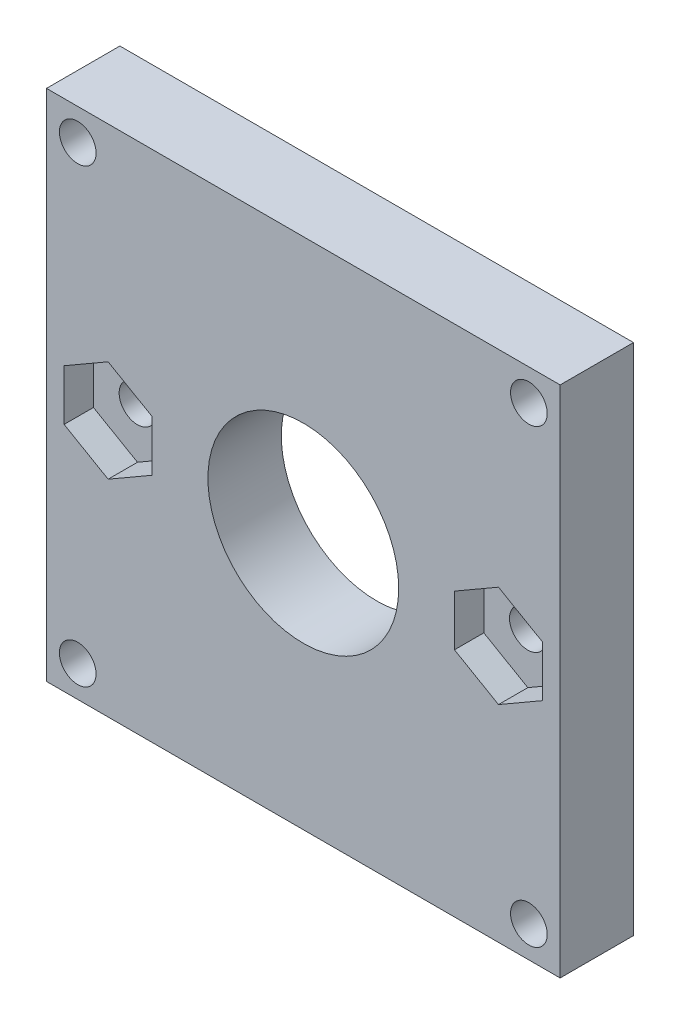
SolidWorks part; units mm, degrees
ref_plane "Alzado" through (0, 0, 0) normal (0, 0, 1) x (1, 0, 0)
ref_plane "Planta" through (0, 0, 0) normal (0, 1, 0) x (1, 0, 0)
ref_plane "Vista lateral" through (0, 0, 0) normal (1, 0, 0) x (0, 0, -1)
sketch "Croquis1" plane through (0, 0, 0) normal (0, 0, 1) x (1, 0, 0)
  line L0 (-17.5, 17.5) -> (-17.5, 13.25) construction
  line L1 (17.5, -17.5) -> (-17.5, -17.5)
  line L2 (17.5, -17.5) -> (17.5, 17.5)
  line L3 (17.5, 17.5) -> (-17.5, 17.5)
  line L4 (-17.5, -17.5) -> (-17.5, 17.5)
  line L5 (17.5, -17.5) -> (-17.5, 17.5) construction
  line L6 (17.5, 17.5) -> (-17.5, -17.5) construction
  line L7 (-17.5, 13.25) -> (-15.37, 13.25) construction
  line L8 (-15.37, 13.25) -> (-15.37, 15.37) construction
  line L9 (17.5, 13.25) -> (15.37, 13.25) construction
  line L10 (15.37, 13.25) -> (15.37, 15.37) construction
  line L11 (15.37, -17.5) -> (15.37, -15.37) construction
  line L12 (-17.5, -15.37) -> (-15.37, -15.37) construction
  line L13 (-13.3, 0) -> (13.3, 0)
  circle A0 centre (-15.37, 15.37) radius 1.25
  circle A1 centre (15.37, 15.37) radius 1.25
  circle A2 centre (15.37, -15.37) radius 1.25
  circle A3 centre (-15.37, -15.37) radius 1.25
  circle A4 centre (0, 0) radius 6.5
  circle A5 centre (13.3, 0) radius 1.25
  circle A6 centre (-13.3, 0) radius 1.25
  point P0 (0, 0)
  point P24 (0, 0)
  dimension "D5" = 2.5
  dimension "D8" = 2.5
  dimension "D10" = 2.5
  dimension "D12" = 2.5
  dimension "D13" = 13
  dimension "D15" = 2.5
  dimension "D16" = 1.25
  dimension "D1" = 35
  dimension "D2" = 4.25
  dimension "D3" = 2.13
  dimension "D4" = 2.12
  dimension "D6" = 2.13
  dimension "D7" = 2.12
  dimension "D9" = 2.13
  dimension "D11" = 2.13
  dimension "D14" = 13.3
extrude "Saliente-Extruir1" add sketch "Croquis1" along normal blind 5
sketch "Croquis2" plane through (0, 0, 5) normal (0, 0, 1) x (1, 0, 0)
  line L1 (-13.3, 3.4641) -> (-16.3, 1.7321)
  line L2 (-16.3, 1.7321) -> (-16.3, -1.7321)
  line L3 (-16.3, -1.7321) -> (-13.3, -3.4641)
  line L4 (-13.3, -3.4641) -> (-10.3, -1.7321)
  line L5 (-10.3, -1.7321) -> (-10.3, 1.7321)
  line L6 (-10.3, 1.7321) -> (-13.3, 3.4641)
  line L7 (13.3, 3.4641) -> (10.3, 1.7321)
  line L8 (10.3, 1.7321) -> (10.3, -1.7321)
  line L9 (10.3, -1.7321) -> (13.3, -3.4641)
  line L10 (13.3, -3.4641) -> (16.3, -1.7321)
  line L11 (16.3, -1.7321) -> (16.3, 1.7321)
  line L12 (16.3, 1.7321) -> (13.3, 3.4641)
  circle A0 centre (-13.3, 0) radius 3 construction
  circle A1 centre (13.3, 0) radius 3 construction
extrude "Cortar-Extruir1" cut sketch "Croquis2" against normal blind 2
